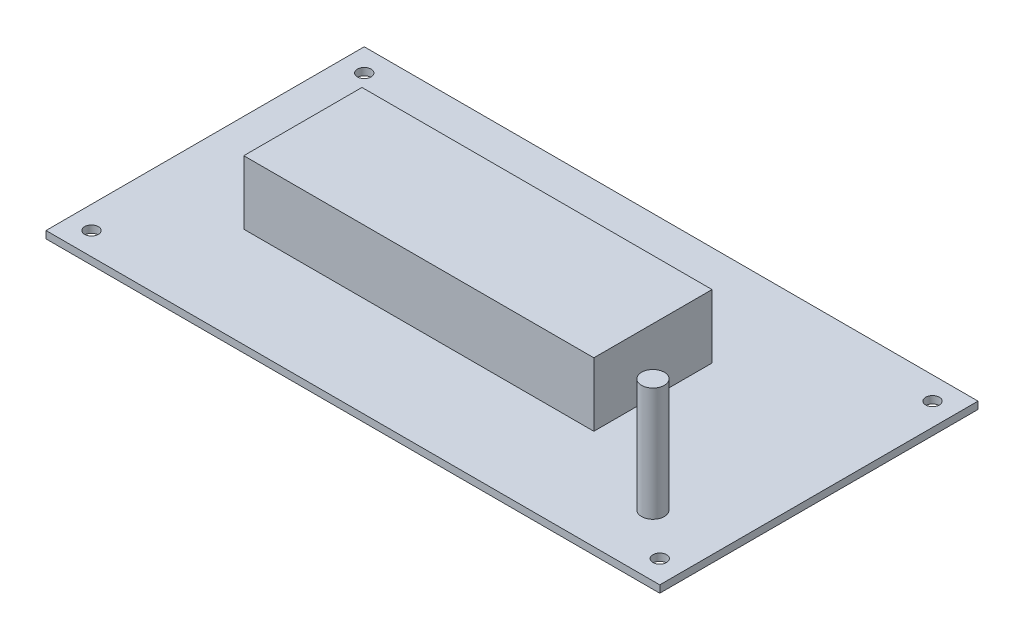
SolidWorks part; units mm, degrees
ref_plane "Front" through (0, 0, 0) normal (0, 0, 1) x (1, 0, 0)
ref_plane "Top" through (0, 0, 0) normal (0, 1, 0) x (1, 0, 0)
ref_plane "Right" through (0, 0, 0) normal (1, 0, 0) x (0, 0, -1)
sketch "Sketch1" plane through (0, 0, 0) normal (0, 1, 0) x (1, 0, 0)
  line L1 (-67.5, -35) -> (67.5, -35)
  line L2 (-67.5, -35) -> (-67.5, 35)
  line L3 (-67.5, 35) -> (67.5, 35)
  line L4 (67.5, -35) -> (67.5, 35)
  line L5 (-67.5, -35) -> (67.5, 35) construction
  line L6 (-67.5, 35) -> (67.5, -35) construction
  point P0 (0, 0)
  dimension "D1" = 135
  dimension "D2" = 70
extrude "Boss-Extrude1" add sketch "Sketch1" along normal blind 1.6
sketch "Sketch2" plane through (0, 1.6, 0) normal (0, 1, 0) x (1, 0, 0)
  line L0 (67.5, 35) -> (-67.5, 35) construction
  line L1 (-67.5, 35) -> (-67.5, -35) construction
  line L2 (0, 35) -> (0, 0) construction
  line L3 (0, 0) -> (-67.5, 0) construction
  circle A0 centre (-62.5, 30) radius 1.5
  circle A1 centre (62.5, 30) radius 1.5
  circle A2 centre (-62.5, 30) radius 1.5
  circle A3 centre (62.5, 30) radius 1.5
  circle A4 centre (-62.5, 30) radius 1.5
  circle A5 centre (62.5, 30) radius 1.5
  circle A6 centre (-62.5, 30) radius 1.5
  circle A7 centre (62.5, 30) radius 1.5
  circle A8 centre (62.5, -30) radius 1.5
  circle A9 centre (-62.5, -30) radius 1.5
  dimension "D1" = 3
  dimension "D2" = 5
  dimension "D3" = 5
extrude "Cut-Extrude1" cut sketch "Sketch2" against normal up to next contours A1 | A0 | A9 | A8
sketch "Sketch3" plane through (0, 1.6, 0) normal (0, 1, 0) x (1, 0, 0)
  circle A0 centre (52.5, -21.5) radius 2.5
  circle A1 centre (62.5, -30) radius 1.5 construction
  dimension "D1" = 8.5
  dimension "D2" = 10
  dimension "D3" = 5
extrude "Boss-Extrude2" add sketch "Sketch3" along normal blind 25
sketch "Sketch4" plane through (0, 1.6, 0) normal (0, 1, 0) x (1, 0, 0)
  line L1 (-46, 13) -> (31, 13)
  line L2 (-46, 13) -> (-46, -13)
  line L3 (-46, -13) -> (31, -13)
  line L4 (31, 13) -> (31, -13)
  line L5 (-46, 13) -> (31, -13) construction
  line L6 (-46, -13) -> (31, 13) construction
  circle A0 centre (-62.5, 30) radius 1.5 construction
  point P4 (-7.5, 0)
  dimension "D1" = 26
  dimension "D2" = 77
  dimension "D3" = 17
  dimension "D4" = 16.5
extrude "Boss-Extrude3" add sketch "Sketch4" along normal blind 14
